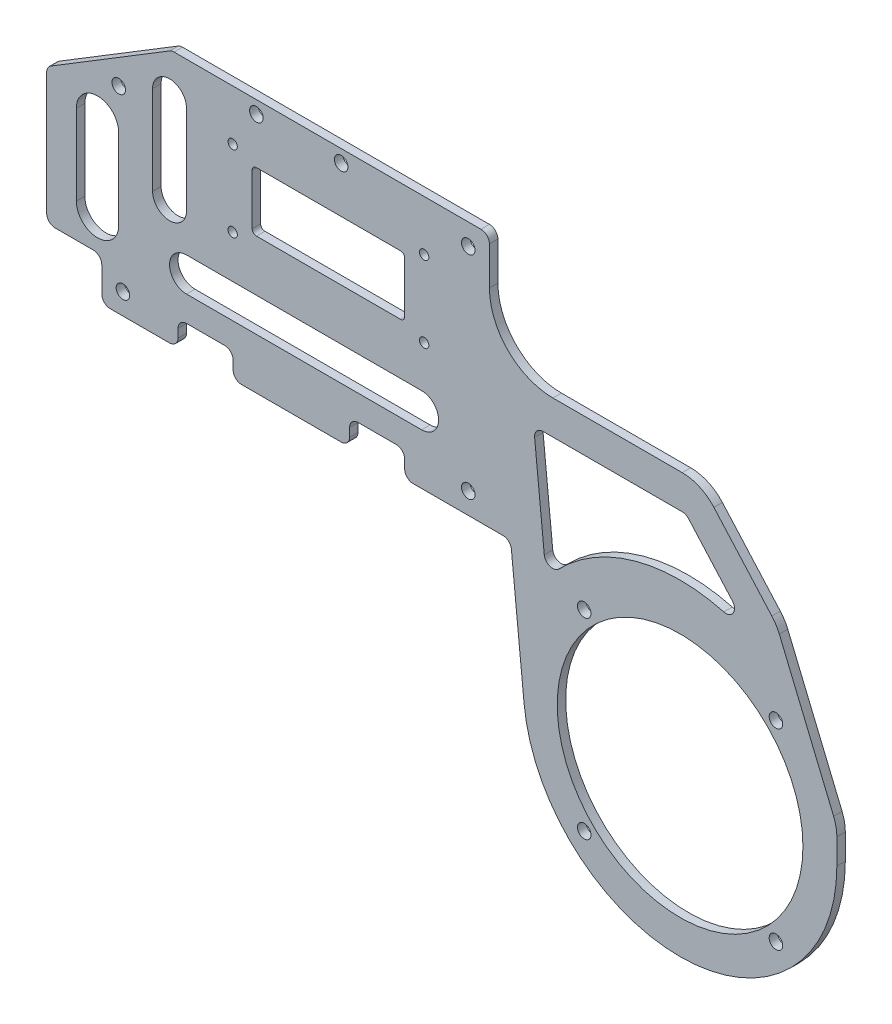
SolidWorks part; units mm, degrees
material "Thornel Mat VMA"
ref_plane "前视基准面" through (0, 0, 0) normal (0, 0, 1) x (1, 0, 0)
ref_plane "上视基准面" through (0, 0, 0) normal (0, 1, 0) x (1, 0, 0)
ref_plane "右视基准面" through (0, 0, 0) normal (1, 0, 0) x (0, 0, -1)
sketch "草图1" plane through (0, 0, 0) normal (0, 0, 1) x (1, 0, 0)
  line L0 (0, 34) -> (0, 60)
  line L1 (0, 60) -> (-75, 60)
  line L2 (-75, 60) -> (-104.5, 42)
  line L3 (-104.5, 42) -> (-104.5, 10)
  line L4 (-104.5, 10) -> (-91.5, 10)
  line L5 (-91.5, 10) -> (-91.5, 0)
  line L6 (-91.5, 0) -> (-73.5, 0)
  line L7 (0, 34) -> (50, 34)
  line L11 (5, 0) -> (0, 0)
  line L12 (-47, -28.2) -> (122.317, -28.2) construction
  line L13 (82, -28.2) -> (82, -2)
  line L14 (-73.5, 0) -> (-73.5, 6)
  line L15 (-73.5, 6) -> (-60.5, 6)
  line L16 (-60.5, 6) -> (-60.5, 0)
  line L18 (-60.5, 0) -> (-33, 0)
  line L19 (-33, 0) -> (-33, 6)
  line L20 (-33, 6) -> (-20, 6)
  line L21 (-20, 6) -> (-20, 0)
  line L22 (0, 0) -> (0, 10) construction
  line L23 (-20, 0) -> (0, 0)
  line L24 (5, 0) -> (8.1831, -31.8764)
  line L25 (82, -2) -> (50, 34)
  circle A0 centre (-86.5, 5) radius 1.6
  circle A1 centre (-5, 5) radius 1.6
  circle A2 centre (45, -28.2) radius 29
  arc A3 (8.1831, -31.8764) -> (82, -28.2) centre (45, -28.2) ccw
  circle A4 centre (-35, 57) radius 1.6
  circle A5 centre (-55, 57) radius 1.6
  circle A6 centre (-87.5, 46.5156) radius 1.6
  circle A7 centre (-15.4, 48.1) radius 1.1
  circle A8 centre (-15.4, 30.1) radius 1.1
  circle A9 centre (-60.6, 48.1) radius 1.1
  circle A10 centre (-60.6, 30.1) radius 1.1
  circle A11 centre (-5, 55) radius 1.6
  dimension "D7" = 3.2
  dimension "D8" = 3.2
  dimension "D10" = 58
  dimension "D12" = 74
  dimension "D22" = 3.2
  dimension "D23" = 3.2
  dimension "D24" = 3.2
  dimension "D25" = 2.2
  dimension "D26" = 2.2
  dimension "D27" = 2.2
  dimension "D28" = 2.2
  dimension "D1" = 91.5
  dimension "D2" = 60
  dimension "D3" = 10
  dimension "D4" = 13
  dimension "D5" = 75
  dimension "D6" = 32
  dimension "D9" = 26
  dimension "D11" = 45
  dimension "D13" = 18
  dimension "D14" = 6
  dimension "D15" = 13
  dimension "D16" = 20
  dimension "D17" = 6
  dimension "D18" = 13
  dimension "D19" = 5
  dimension "D20" = 36
  dimension "D21" = 50
extrude "凸台-拉伸1" add sketch "草图1" along normal blind 2
fillet "圆角1" radius 15 1 edges at (0, 34, 1)
fillet "圆角2" radius 10 2 edges at (50, 34, 1) (82, -2, 1)
fillet "圆角3" radius 2 15 edges at (-33, 6, 1) (-33, 0, 1) (-20, 0, 1) (-20, 6, 1) (-60.5, 0, 1) (-60.5, 6, 1) (-73.5, 6, 1) (-73.5, 0, 1) (-91.5, 0, 1) (-91.5, 10, 1) (-104.5, 10, 1) (-104.5, 42, 1) (-75, 60, 1) (0, 60, 1) (5, 0, 1)
sketch "草图2" plane through (0, 0, 2) normal (0, 0, 1) x (1, 0, 0)
  line L0 (45, -28.2) -> (66.9366, -28.2) construction
  line L1 (45, -28.2) -> (67.6274, -50.8274) construction
  circle A0 centre (45, -28.2) radius 32 construction
  circle A2 centre (67.6274, -50.8274) radius 1.6
  circle A3 centre (22.3726, -50.8274) radius 1.6
  circle A4 centre (22.3726, -5.5726) radius 1.6
  circle A5 centre (67.6274, -5.5726) radius 1.6
  point P15 (45, -28.2)
  dimension "D1" = 64
  dimension "D2" = 45
  dimension "D3" = 3.2
  dimension "D4" = 4
extrude "切除-拉伸1" cut sketch "草图2" against normal through all
sketch "草图3" plane through (0, 0, 0) normal (0, 0, -1) x (-1, 0, 0)
  line L0 (20, 45.1) -> (20, 33.1) construction
  line L1 (55, 46.1) -> (21, 46.1) construction
  line L2 (21, 32.1) -> (55, 32.1) construction
  line L3 (56, 33.1) -> (56, 45.1) construction
  line L4 (20, 45.1) -> (20, 33.1)
  line L5 (55, 46.1) -> (21, 46.1)
  line L6 (21, 32.1) -> (55, 32.1)
  line L7 (56, 33.1) -> (56, 45.1)
  line L8 (71.5, 20) -> (16, 20) construction
  line L9 (16, 12) -> (71.5, 12) construction
  line L10 (71.5, 20) -> (16, 20)
  line L11 (16, 12) -> (71.5, 12)
  line L12 (79.5, 50) -> (79.5, 29) construction
  line L13 (71.5, 29) -> (71.5, 50) construction
  line L14 (97.5, 37) -> (97.5, 18) construction
  line L15 (87.5, 18) -> (87.5, 37) construction
  line L16 (79.5, 50) -> (79.5, 29)
  line L17 (71.5, 29) -> (71.5, 50)
  line L18 (97.5, 37) -> (97.5, 18)
  line L19 (87.5, 18) -> (87.5, 37)
  line L20 (-45.5093, 26) -> (-12.6532, 26)
  line L21 (-10.663, 23.8013) -> (-12.9469, 0.9307)
  line L22 (-5.1799, -1.8013) -> (-8.1831, -31.8764) construction
  line L23 (-47.0042, 25.3287) -> (-57.336, 13.7054)
  line L25 (-79.4741, 0.8416) -> (-52.9834, 30.6436) construction
  line L26 (-45.5093, 34) -> (-15, 34) construction
  arc A0 (20, 33.1) -> (21, 32.1) centre (21, 33.1) ccw construction
  arc A1 (21, 46.1) -> (20, 45.1) centre (21, 45.1) ccw construction
  arc A2 (56, 45.1) -> (55, 46.1) centre (55, 45.1) ccw construction
  arc A3 (55, 32.1) -> (56, 33.1) centre (55, 33.1) ccw construction
  arc A4 (20, 33.1) -> (21, 32.1) centre (21, 33.1) ccw
  arc A5 (21, 46.1) -> (20, 45.1) centre (21, 45.1) ccw
  arc A6 (56, 45.1) -> (55, 46.1) centre (55, 45.1) ccw
  arc A7 (55, 32.1) -> (56, 33.1) centre (55, 33.1) ccw
  arc A8 (16, 20) -> (16, 12) centre (16, 16) ccw construction
  arc A9 (71.5, 12) -> (71.5, 20) centre (71.5, 16) ccw construction
  arc A10 (16, 20) -> (16, 12) centre (16, 16) ccw
  arc A11 (71.5, 12) -> (71.5, 20) centre (71.5, 16) ccw
  arc A12 (79.5, 50) -> (71.5, 50) centre (75.5, 50) ccw construction
  arc A13 (71.5, 29) -> (79.5, 29) centre (75.5, 29) ccw construction
  arc A14 (87.5, 18) -> (97.5, 18) centre (92.5, 18) ccw construction
  arc A15 (97.5, 37) -> (87.5, 37) centre (92.5, 37) ccw construction
  arc A16 (79.5, 50) -> (71.5, 50) centre (75.5, 50) ccw
  arc A17 (71.5, 29) -> (79.5, 29) centre (75.5, 29) ccw
  arc A18 (87.5, 18) -> (97.5, 18) centre (92.5, 18) ccw
  arc A19 (97.5, 37) -> (87.5, 37) centre (92.5, 37) ccw
  arc A20 (-16.3685, -0.2672) -> (-55.3249, 10.4445) centre (-45, -28.2) ccw
  arc A21 (-12.6532, 26) -> (-10.663, 23.8013) centre (-12.6532, 24) cw
  arc A22 (-45.5093, 26) -> (-47.0042, 25.3287) centre (-45.5093, 24) ccw
  arc A23 (-12.9469, 0.9307) -> (-16.3685, -0.2672) centre (-14.937, 1.1294) cw
  arc A24 (-57.336, 13.7054) -> (-55.3249, 10.4445) centre (-55.8412, 12.3767) ccw
  dimension "D1" = 80
  dimension "D5" = 2
  dimension "D2" = 8
  dimension "D3" = 8
  dimension "D4" = 8
extrude "切除-拉伸2" cut sketch "草图3" against normal through all
sketch "草图4" plane through (0, 0, 2) normal (0, 0, 1) x (1, 0, 0)
  line L0 (67.7778, 14) -> (82, -20.2)
  line L1 (79.4741, 0.8416) -> (52.9834, 30.6436) construction
  line L2 (82, -28.2) -> (82, -5.802) construction
  line L3 (45.5093, 34) -> (15, 34) construction
  line L4 (67.7778, 14) -> (96.2507, 10.5665)
  line L5 (96.2507, 10.5665) -> (82, -20.2)
  circle A0 centre (45, -28.2) radius 29 construction
  dimension "D1" = 8
  dimension "D2" = 20
extrude "切除-拉伸3" cut sketch "草图4" against normal through all
fillet "圆角4" radius 10 2 edges at (82, -20.2, 1) (67.7778, 14, 1)
